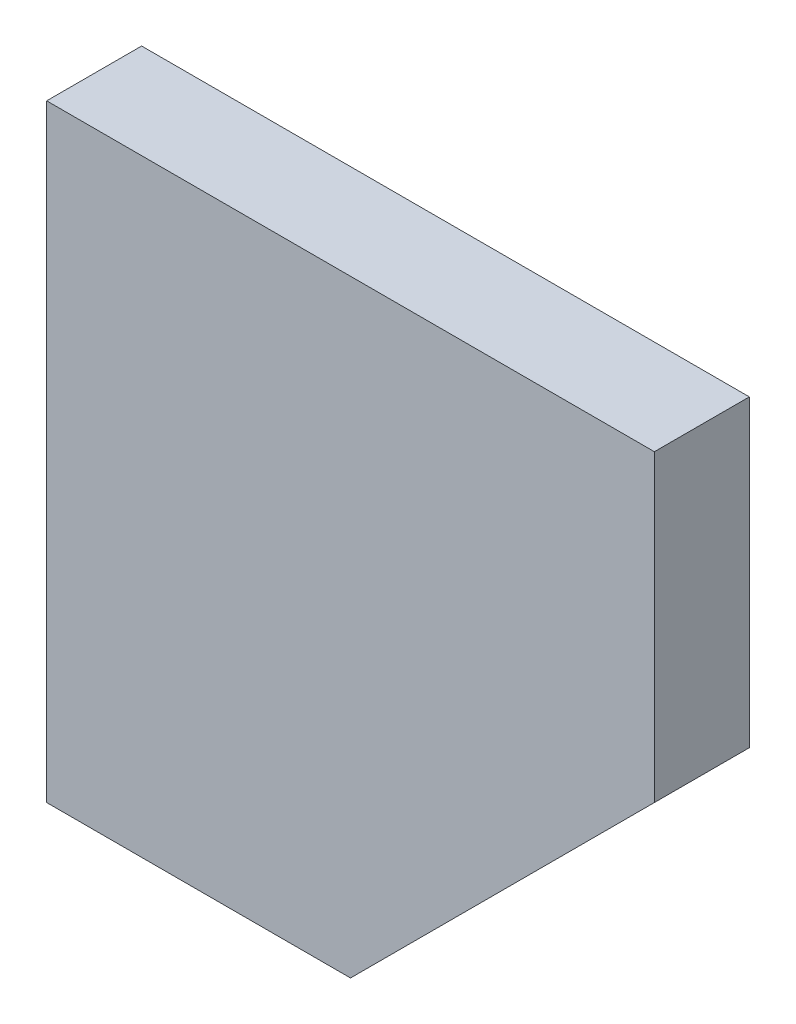
SolidWorks part; units mm, degrees
ref_plane "Front Plane" through (0, 0, 0) normal (0, 0, 1) x (1, 0, 0)
ref_plane "Top Plane" through (0, 0, 0) normal (0, 1, 0) x (1, 0, 0)
ref_plane "Right Plane" through (0, 0, 0) normal (1, 0, 0) x (0, 0, -1)
sketch "Sketch1" plane through (0, 0, 0) normal (0, 0, 1) x (1, 0, 0)
  line L0 (0, 0) -> (0, 50.8)
  line L1 (0, 50.8) -> (50.8, 50.8)
  line L2 (50.8, 50.8) -> (50.8, 25.4)
  line L3 (50.8, 25.4) -> (25.4, 0)
  line L4 (25.4, 0) -> (0, 0)
  dimension "D1" = 50.8
  dimension "D2" = 50.8
  dimension "D3" = 25.4
  dimension "D4" = 25.4
extrude "Boss-Extrude1" add sketch "Sketch1" along normal blind 7.9375
